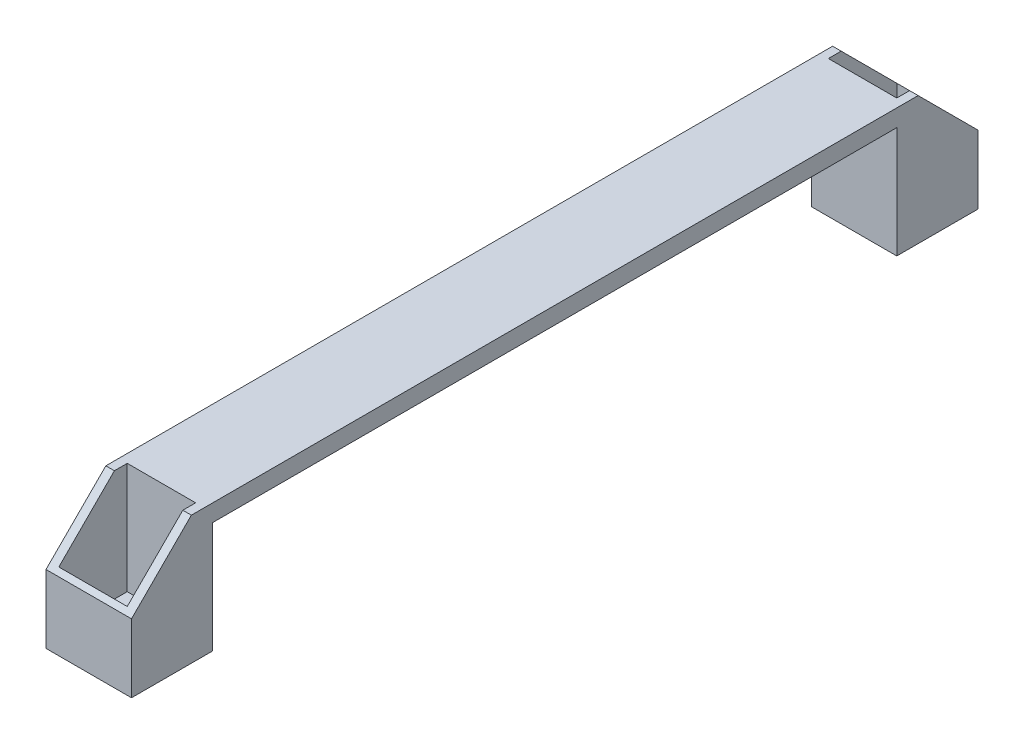
SolidWorks part; units mm, degrees
ref_plane "Front Plane" through (0, 0, 0) normal (0, 0, 1) x (1, 0, 0)
ref_plane "Top Plane" through (0, 0, 0) normal (0, 1, 0) x (1, 0, 0)
ref_plane "Right Plane" through (0, 0, 0) normal (1, 0, 0) x (0, 0, -1)
sketch "Sketch2" plane through (0, 0, 0) normal (0, 1, 0) x (1, 0, 0)
  line L1 (0, 0) -> (20, 0)
  line L2 (0, 0) -> (0, 20)
  line L3 (0, 20) -> (20, 20)
  line L4 (20, 0) -> (20, 20)
  line L5 (0, -160) -> (20, -160)
  line L6 (0, -160) -> (0, -180)
  line L7 (0, -180) -> (20, -180)
  line L8 (20, -160) -> (20, -180)
  dimension "D1" = 20
  dimension "D2" = 20
  dimension "D3" = 20
  dimension "D4" = 20
  dimension "D5" = 200
  dimension "D6" = 20
extrude "Boss-Extrude1" add sketch "Sketch2" along normal blind 30
sketch "Sketch3" plane through (0, 30, 0) normal (0, 1, 0) x (1, 0, 0)
  line L0 (20, 20) -> (0, 20) construction
  line L1 (2, 18) -> (18, 18)
  line L2 (2, 18) -> (2, 2)
  line L3 (2, 2) -> (18, 2)
  line L4 (18, 18) -> (18, 2)
  line L5 (0, 20) -> (0, 0) construction
  line L6 (0, 0) -> (20, 0) construction
  line L7 (20, 0) -> (20, 20) construction
  line L8 (0, -160) -> (0, -180) construction
  line L9 (2, -162) -> (18, -162)
  line L10 (2, -162) -> (2, -178)
  line L11 (2, -178) -> (18, -178)
  line L12 (18, -162) -> (18, -178)
  line L13 (20, -180) -> (20, -160) construction
  line L14 (20, -160) -> (0, -160) construction
  line L15 (0, -180) -> (20, -180) construction
  dimension "D1" = 2
  dimension "D2" = 2
  dimension "D3" = 2
  dimension "D4" = 2
  dimension "D5" = 2
  dimension "D6" = 2
  dimension "D7" = 2
  dimension "D8" = 2
extrude "Cut-Extrude1" cut sketch "Sketch3" against normal blind 26
sketch "Sketch4" plane through (0, 4, 0) normal (0, 1, 0) x (1, 0, 0)
  line L0 (0, -180) -> (20, -180) construction
  line L1 (0, -160) -> (0, -180) construction
  line L2 (0, 0) -> (20, 0) construction
  line L3 (0, 20) -> (0, 0) construction
  circle A0 centre (10, -170) radius 3
  circle A1 centre (10, 10) radius 3
  dimension "D1" = 6
  dimension "D2" = 10
  dimension "D3" = 10
  dimension "D4" = 10
  dimension "D5" = 10
  dimension "D6" = 6
extrude "Cut-Extrude2" cut sketch "Sketch4" against normal blind 56
sketch "Sketch7" plane through (0, 0, 160) normal (0, 0, -1) x (-1, 0, 0)
  line L0 (-20, 30) -> (-20, 0) construction
  line L1 (0, 30) -> (-20, 30)
  line L2 (0, 30) -> (0, 26)
  line L3 (0, 26) -> (-20, 26)
  line L4 (-20, 30) -> (-20, 26)
  dimension "D1" = 4
extrude "Boss-Extrude2" add sketch "Sketch7" along normal blind 160
sketch "Sketch9" plane through (20, 0, 0) normal (1, 0, 0) x (0, 0, -1)
  line L0 (-180, 15) -> (-165, 30)
  line L1 (-180, 30) -> (-180, 0) construction
  line L2 (-180, 30) -> (20, 30) construction
  line L3 (-165, 30) -> (-180, 30)
  line L4 (-180, 30) -> (-180, 15)
  line L5 (20, 15) -> (5, 30)
  line L6 (20, 30) -> (20, 0) construction
  line L7 (5, 30) -> (20, 30)
  line L8 (20, 30) -> (20, 15)
extrude "Cut-Extrude5" cut sketch "Sketch9" against normal blind 140
sketch "Sketch10" plane through (20, 0, 0) normal (1, 0, 0) x (0, 0, -1)
  line L1 (-180, 0) -> (-179, 0)
  line L2 (-180, 0) -> (-180, 37.3585)
  line L3 (-180, 37.3585) -> (-179, 37.3585)
  line L4 (-179, 0) -> (-179, 37.3585)
  line L5 (20, 0) -> (19, 0)
  line L6 (20, 0) -> (20, 37.3585)
  line L7 (20, 37.3585) -> (19, 37.3585)
  line L8 (19, 0) -> (19, 37.3585)
  dimension "D1" = 1
  dimension "D2" = 1
extrude "Cut-Extrude6" cut sketch "Sketch10" against normal blind 140
